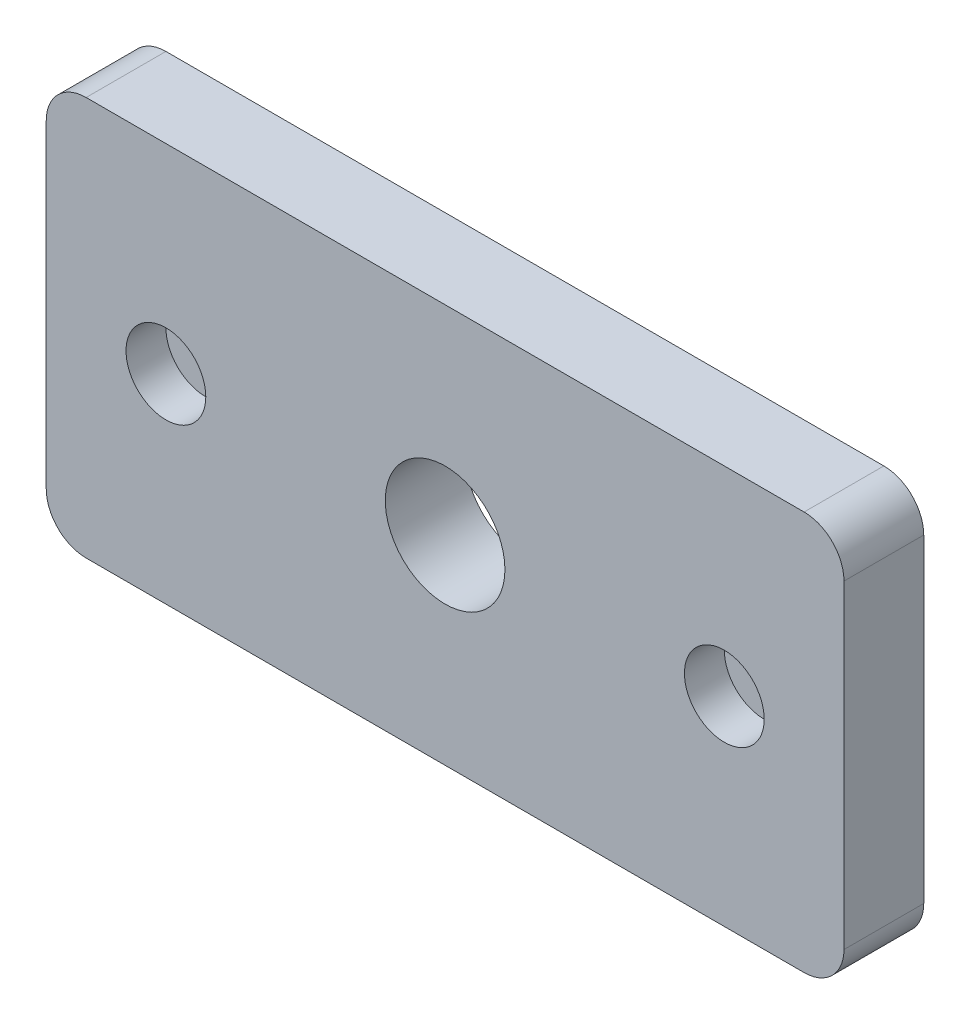
SolidWorks part; units mm, degrees
ref_plane "Front Plane" through (0, 0, 0) normal (0, 0, 1) x (1, 0, 0)
ref_plane "Top Plane" through (0, 0, 0) normal (0, 1, 0) x (1, 0, 0)
ref_plane "Right Plane" through (0, 0, 0) normal (1, 0, 0) x (0, 0, -1)
sketch "Sketch1" plane through (0, 0, 0) normal (0, 0, 1) x (1, 0, 0)
  line L1 (-5000, -2500) -> (5000, -2500)
  line L2 (-5000, -2500) -> (-5000, 2500)
  line L3 (-5000, 2500) -> (5000, 2500)
  line L4 (5000, -2500) -> (5000, 2500)
  line L5 (-5000, -2500) -> (5000, 2500) construction
  line L6 (-5000, 2500) -> (5000, -2500) construction
  point P0 (0, 0)
  dimension "D1" = 5000
  dimension "D2" = 2500
extrude "Boss-Extrude1" add sketch "Sketch1" along normal blind 1000
fillet "Fillet1" radius 500 1 edges at (-5000, 2500, 500)
fillet "Fillet2" radius 500 3 edges at (-5000, -2500, 500) (5000, -2500, 500) (5000, 2500, 500)
sketch "Sketch2" plane through (0, 0, 1000) normal (0, 0, 1) x (1, 0, 0)
  line L0 (4500, 2500) -> (-4500, 2500) construction
  circle A0 centre (-3500, 0) radius 500
  circle A1 centre (3500, 0) radius 500
  dimension "D3" = 1000
  dimension "D4" = 1000
  dimension "D1" = 3500
  dimension "D2" = 3500
  dimension "D5" = 2500
  dimension "D6" = 2500
extrude "Cut-Extrude1" cut sketch "Sketch2" against normal blind 500
sketch "Sketch3" plane through (0, 0, 1000) normal (0, 0, 1) x (1, 0, 0)
  circle A0 centre (0, 0) radius 750
  dimension "D1" = 1500
extrude "Cut-Extrude2" cut sketch "Sketch3" against normal through all
